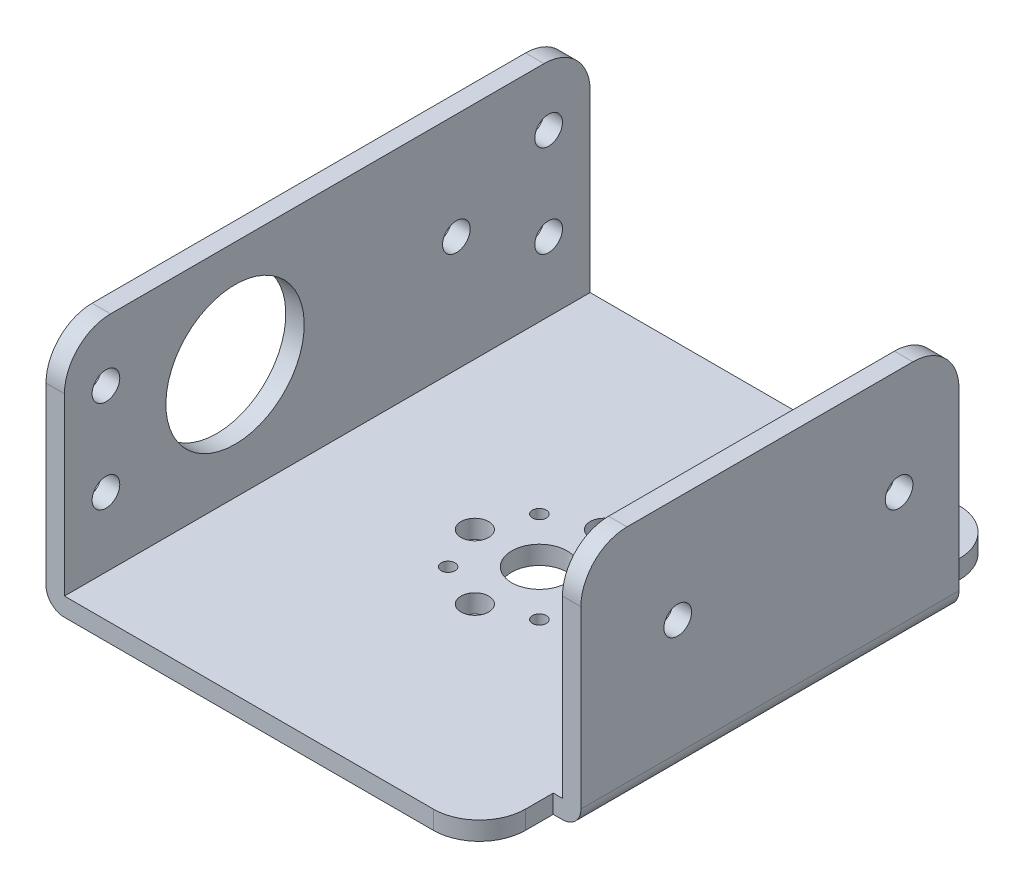
SolidWorks part; units mm, degrees
material "普通碳钢"
ref_plane "前视" through (0, 0, 0) normal (0, 0, 1) x (1, 0, 0)
ref_plane "上视" through (0, 0, 0) normal (0, 1, 0) x (1, 0, 0)
ref_plane "右视" through (0, 0, 0) normal (1, 0, 0) x (0, 0, -1)
sketch "草图1" plane through (0, 0, 0) normal (0, 0, 1) x (1, 0, 0)
  line L0 (0, 0) -> (0, -26)
  line L1 (0, -26) -> (50, -26)
  line L2 (2, 0) -> (2, -24)
  line L3 (2, -24) -> (48, -24)
  line L4 (0, 0) -> (2, 0)
  line L8 (50, -26) -> (50, 0)
  line L9 (50, 0) -> (48, 0)
  line L10 (48, -24) -> (48, 0)
  line L11 (0, -26) -> (50, -26) construction
  line L12 (2, -24) -> (50, -24) construction
  dimension "D2" = 50
  dimension "D3" = 26
  dimension "D4" = 2
  dimension "D5" = 26
  dimension "D1" = 2
extrude "凸台-拉伸1" add sketch "草图1" along normal blind 57
sketch "草图2" plane through (0, 0, 0) normal (-1, 0, 0) x (0, 0, 1)
  line L0 (-12.5584, -11.5) -> (57, -11.5) construction
  line L1 (57, 0) -> (57, -26) construction
  line L2 (28.5, -26) -> (28.5, 0) construction
  line L3 (57, -26) -> (0, -26) construction
  line L4 (57, 0) -> (0, 0) construction
  circle A0 centre (38.5, -11.5) radius 7.5
  circle A1 centre (14.5, -11.5) radius 1.5
  dimension "D1" = 24
  dimension "D2" = 3
  dimension "D3" = 15
  dimension "D4" = 11.5
  dimension "D5" = 18.5
extrude "切除-拉伸1" cut sketch "草图2" against normal blind 27
sketch "草图3" plane through (2, 0, 0) normal (1, 0, 0) x (0, 0, -1)
  line L0 (-38.5, -11.5) -> (-14.5, -11.5) construction
  line L1 (-28.5, -26) -> (-28.5, 0) construction
  line L2 (-57, -26) -> (0, -26) construction
  line L3 (-57, 0) -> (0, 0) construction
  circle A0 centre (-52.5, -6.5) radius 3 construction
  circle A1 centre (-4.5, -6.5) radius 3 construction
  circle A2 centre (-4.5, -16.5) radius 3 construction
  circle A3 centre (-52.5, -16.5) radius 3 construction
  circle A5 centre (-4.5, -6.5) radius 1.5
  circle A6 centre (-4.5, -16.5) radius 1.5
  circle A7 centre (-52.5, -16.5) radius 1.5
  circle A8 centre (-52.5, -6.5) radius 1.5
  dimension "D1" = 48
  dimension "D2" = 6
  dimension "D4" = 10
  dimension "D5" = 3
extrude "切除-拉伸2" cut sketch "草图3" against normal blind 10
sketch "草图4" plane through (0, -24, 0) normal (0, 1, 0) x (1, 0, 0)
  line L0 (32, -28.5) -> (18, -28.5) construction
  line L1 (0, -31) -> (0, -46) construction
  line L2 (2, -57) -> (2, 0) construction
  line L3 (25, -57) -> (25, 0) construction
  line L4 (48, -57) -> (2, -57) construction
  line L5 (48, 0) -> (2, 0) construction
  line L6 (0, -57) -> (0, 0) construction
  line L7 (50, -28.5) -> (0, -28.5) construction
  line L8 (0, -13) -> (0, -16) construction
  line L9 (0, -14.5) -> (2, -14.5) construction
  line L10 (0, -38.5) -> (2, -38.5) construction
  line L11 (1, -14.5) -> (1, -38.5) construction
  line L12 (50, -57) -> (50, 0) construction
  line L13 (20.0503, -23.5503) -> (25, -28.5) construction
  line L14 (0, 0) -> (50, 0) construction
  line L15 (50, 0) -> (25, 0) construction
  line L16 (25, 0) -> (25, -57) construction
  line L17 (48, -57) -> (2, -57) construction
  circle A0 centre (25, -28.5) radius 7 construction
  circle A1 centre (18, -28.5) radius 1.5
  circle A2 centre (25, -21.5) radius 1.5
  circle A3 centre (32, -28.5) radius 1.5
  circle A4 centre (25, -35.5) radius 1.5
  circle A5 centre (25, -28.5) radius 3
  circle A6 centre (20.0503, -23.5503) radius 0.75
  circle A7 centre (29.9497, -23.5503) radius 0.75
  circle A8 centre (29.9497, -33.4497) radius 0.75
  circle A9 centre (20.0503, -33.4497) radius 0.75
  dimension "D1" = 14
  dimension "D2" = 3
  dimension "D4" = 6
  dimension "D5" = 1.5
  dimension "D3" = 45
extrude "切除-拉伸3" cut sketch "草图4" against normal blind 10
sketch "草图5" plane through (48, 0, 0) normal (-1, 0, 0) x (0, 0, 1)
  circle A0 centre (14.5, -11.5) radius 1.5
  circle A1 centre (38.5, -11.5) radius 1.5
  dimension "D1" = 3
  dimension "D2" = 3
extrude "切除-拉伸4" cut sketch "草图5" against normal blind 3
fillet "圆角2" radius 2 2 edges at (50, -26, 28.5) (0, -26, 28.5)
sketch "草图6" plane through (0, -26, 0) normal (0, -1, 0) x (1, 0, 0)
  line L0 (0, 28.5) -> (50, 28.5) construction
  line L1 (0, 0) -> (0, 57) construction
  line L2 (50, 57) -> (50, 0) construction
  line L3 (25, 57) -> (25, 0) construction
  line L4 (2, 57) -> (48, 57) construction
  line L5 (2, 0) -> (48, 0) construction
  line L6 (47, 57) -> (47, 49)
  line L7 (47, 49) -> (50, 49)
  line L8 (50, 49) -> (50, 57)
  line L9 (50, 57) -> (47, 57)
  line L10 (50, 0) -> (47, 0)
  line L11 (50, 8) -> (50, 0)
  line L12 (47, 8) -> (50, 8)
  line L13 (47, 0) -> (47, 8)
  dimension "D1" = 8
  dimension "D2" = 3
extrude "切除-拉伸5" cut sketch "草图6" against normal blind 44
fillet "圆角3" radius 5 6 edges at (47, -25, 57) (47, -25, 0) (49, 0, 8) (49, 0, 49) (1, 0, 57) (1, 0, 0)
